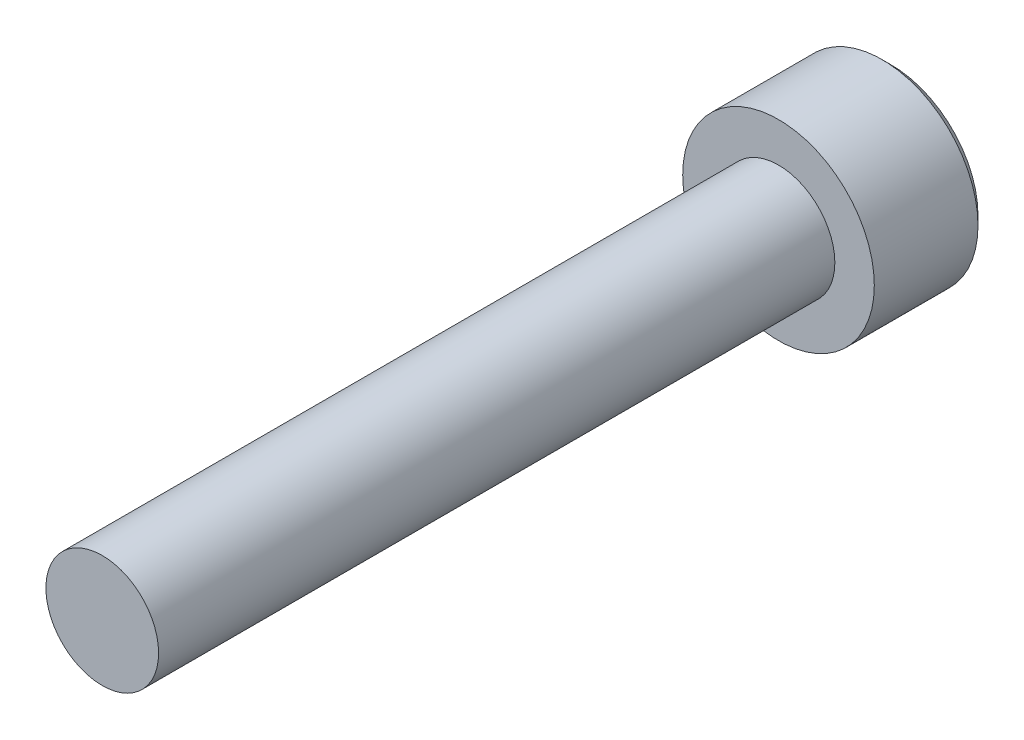
SolidWorks part; units mm, degrees
ref_plane "前视基准面" through (0, 0, 0) normal (0, 0, 1) x (1, 0, 0)
ref_plane "上视基准面" through (0, 0, 0) normal (0, 1, 0) x (1, 0, 0)
ref_plane "右视基准面" through (0, 0, 0) normal (1, 0, 0) x (0, 0, -1)
other "Configuration Table"
sketch "Sk_shank" plane through (0, 0, 0) normal (0, 0, 1) x (1, 0, 0)
  circle A0 centre (0, 0) radius 2.5
extrude "Ext_shank" add sketch "Sk_shank" along normal blind 35
sketch "Sk_head" plane through (0, 0, 0) normal (0, 0, 1) x (1, 0, 0)
  circle A0 centre (0, 0) radius 4.25
extrude "Ext_head" add sketch "Sk_head" along normal blind 5
sketch "Sk_hex" plane through (0, 0, 0) normal (0, 0, 1) x (1, 0, 0)
  line L0 (2.3094, 0) -> (1.1547, 2)
  line L1 (1.1547, 2) -> (-1.1547, 2)
  line L2 (-1.1547, 2) -> (-2.3094, 0)
  line L3 (-2.3094, 0) -> (-1.1547, -2)
  line L4 (-1.1547, -2) -> (1.1547, -2)
  line L5 (1.1547, -2) -> (2.3094, 0)
extrude "Cut_hex" cut sketch "Sk_hex" along normal blind 3
chamfer "Chamfer_head" distance 0.4 angle 45 7 edges at (0, -2, 0) (-1.7321, -1, 0) (-1.7321, 1, 0) (0, 2, 0) (1.7321, 1, 0) (1.7321, -1, 0) (4.25, 0, 0)
